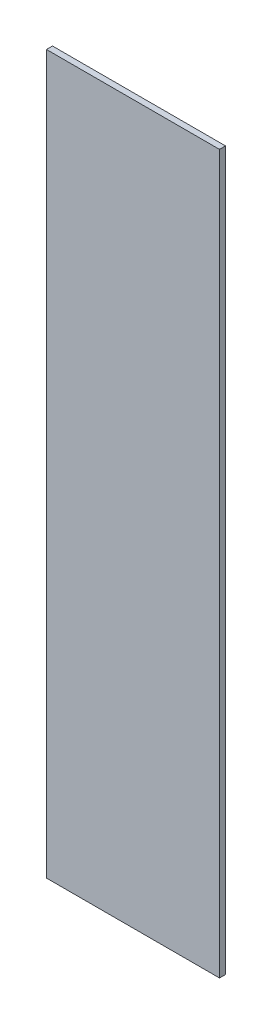
SolidWorks part; units mm, degrees
ref_plane "Ön Düzlem" through (0, 0, 0) normal (0, 0, 1) x (1, 0, 0)
ref_plane "Üst Düzlem" through (0, 0, 0) normal (0, 1, 0) x (1, 0, 0)
ref_plane "Sağ Düzlem" through (0, 0, 0) normal (1, 0, 0) x (0, 0, -1)
sketch "Sketch1" plane through (0, 0, 0) normal (0, 0, 1) x (1, 0, 0)
  line L1 (-57.5, 238.5) -> (57.5, 238.5)
  line L2 (-57.5, 238.5) -> (-57.5, -238.5)
  line L3 (-57.5, -238.5) -> (57.5, -238.5)
  line L4 (57.5, 238.5) -> (57.5, -238.5)
  line L5 (-57.5, 238.5) -> (57.5, -238.5) construction
  line L6 (-57.5, -238.5) -> (57.5, 238.5) construction
  point P0 (0, 0)
  dimension "D1" = 115
  dimension "D2" = 477
extrude "Boss-Extrude1" add sketch "Sketch1" along normal blind 4
